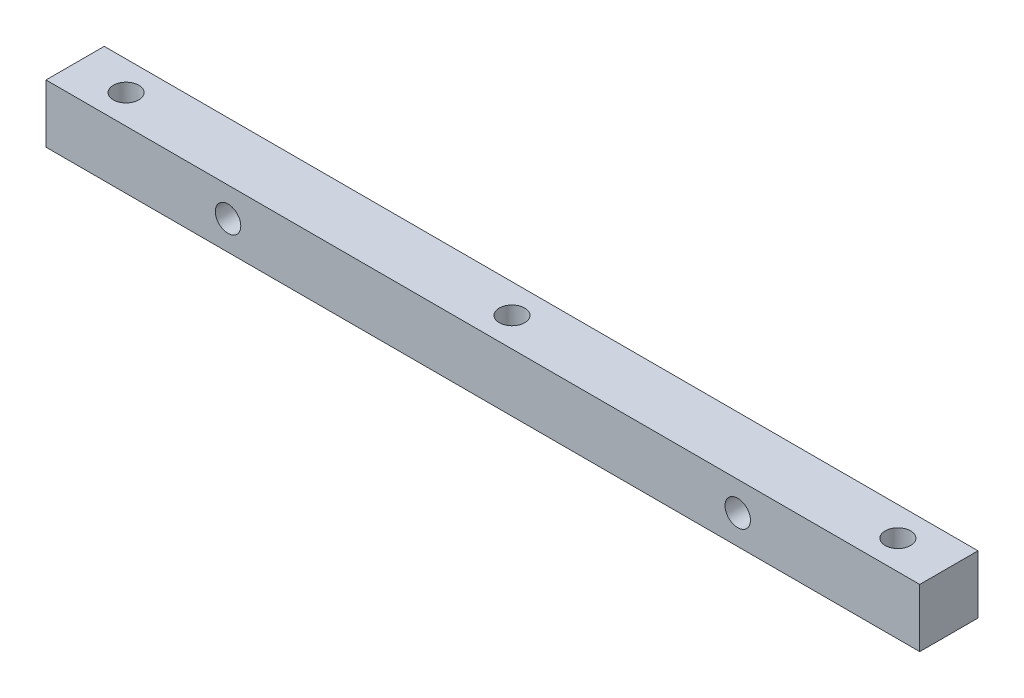
SolidWorks part; units mm, degrees
ref_plane "Ebene vorne" through (0, 0, 0) normal (0, 0, 1) x (1, 0, 0)
ref_plane "Ebene oben" through (0, 0, 0) normal (0, 1, 0) x (1, 0, 0)
ref_plane "Ebene rechts" through (0, 0, 0) normal (1, 0, 0) x (0, 0, -1)
sketch "Skizze1" plane through (0, 0, 0) normal (0, 0, 1) x (1, 0, 0)
  line L0 (-35, 0) -> (35, 0) construction
  line L1 (-60, -4) -> (60, -4)
  line L2 (-60, -4) -> (-60, 4)
  line L3 (-60, 4) -> (60, 4)
  line L4 (60, -4) -> (60, 4)
  line L5 (-60, -4) -> (60, 4) construction
  line L6 (-60, 4) -> (60, -4) construction
  circle A0 centre (-35, 0) radius 1.75
  circle A1 centre (35, 0) radius 1.75
  point P0 (0, 0)
  point P9 (0, 0)
  dimension "D3" = 3.5
  dimension "D4" = 3.5
  dimension "D1" = 8
  dimension "D2" = 70
  dimension "D5" = 120
extrude "Aufsatz-Linear austragen1" add sketch "Skizze1" along normal blind 8
sketch "Skizze2" plane through (0, 4, 0) normal (0, 1, 0) x (1, 0, 0)
  line L0 (0, 0) -> (0, -8) construction
  line L1 (60, -8) -> (-60, -8) construction
  line L2 (0, -4) -> (60, -4) construction
  line L3 (60, -8) -> (60, 0) construction
  circle A0 centre (53, -4) radius 1.75
  circle A1 centre (-53, -4) radius 1.75
  circle A2 centre (0, -4) radius 1.75
  dimension "D1" = 3.5
  dimension "D3" = 3.5
  dimension "D2" = 7
extrude "Schnitt-Linear austragen1" cut sketch "Skizze2" against normal through all
